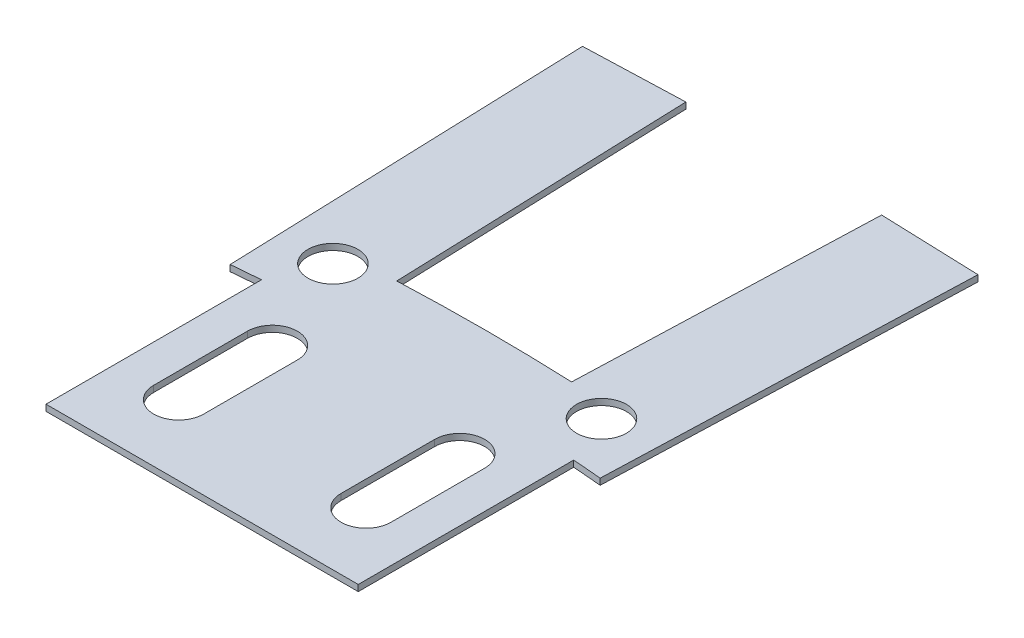
SolidWorks part; units mm, degrees
material "Galvanized Steel"
ref_plane "Front Plane" through (0, 0, 0) normal (0, 0, 1) x (1, 0, 0)
ref_plane "Top Plane" through (0, 0, 0) normal (0, 1, 0) x (1, 0, 0)
ref_plane "Right Plane" through (0, 0, 0) normal (1, 0, 0) x (0, 0, -1)
sketch "Sketch1" plane through (0, 0, 0) normal (0, 1, 0) x (1, 0, 0)
  line L0 (-1000, 0) -> (49000, 0) construction
  line L1 (0, -1000) -> (0, 49000) construction
  line L2 (-500, -866.0254) -> (24500, 42435.2448) construction
  line L3 (-500, 866.0254) -> (24500, -42435.2448) construction
  line L7 (25, 325.8046) -> (25, 291.3046)
  line L8 (25, 291.3046) -> (-25, 291.3046)
  line L9 (29.6237, 325.4167) -> (29.9934, 336.0031)
  line L10 (-25, 325.8046) -> (-25, 291.3046)
  line L11 (29.9934, 336.0031) -> (31.6654, 383.8836)
  line L12 (31.6654, 383.8836) -> (15.6752, 384.442)
  line L13 (15.6752, 384.442) -> (14, 336.4712)
  line L14 (-15.6752, 384.442) -> (-14, 336.4712)
  line L15 (-31.6654, 383.8836) -> (-15.6752, 384.442)
  line L16 (-29.9934, 336.0031) -> (-31.6654, 383.8836)
  line L17 (-29.6237, 325.4167) -> (-29.9934, 336.0031)
  line L18 (-19, 317.5546) -> (-19, 302.5546)
  line L20 (-11, 317.5546) -> (-11, 302.5546)
  line L21 (19, 317.5546) -> (19, 302.5546)
  line L22 (11, 317.5546) -> (11, 302.5546)
  circle A0 centre (0, 0) radius 400 construction
  arc A14 (25, 325.8046) -> (29.6237, 325.4167) centre (0, 0) cw
  arc A15 (-25, 325.8046) -> (-29.6237, 325.4167) centre (0, 0) ccw
  arc A16 (14, 336.4712) -> (-14, 336.4712) centre (0, 0) ccw
  arc A17 (-19, 302.5546) -> (-11, 302.5546) centre (-15, 302.5546) ccw
  circle A19 centre (-21.5, 333.7549) radius 4
  circle A20 centre (21.5, 333.7549) radius 4
  arc A21 (-11, 317.5546) -> (-19, 317.5546) centre (-15, 317.5546) ccw
  arc A22 (19, 302.5546) -> (11, 302.5546) centre (15, 302.5546) cw
  arc A23 (11, 317.5546) -> (19, 317.5546) centre (15, 317.5546) cw
  point P34 (0, 291.3046)
  dimension "D1" = 800
  dimension "D4" = 2
  dimension "D5" = 28
  dimension "D8" = 10
  dimension "D9" = 50
  dimension "D12" = 11.25
  dimension "D13" = 30
  dimension "D14" = 21.5
  dimension "D15" = 8
  dimension "D6" = 16
  dimension "D7" = 336.7623
  dimension "D10" = 8
  dimension "D17" = 8
  dimension "D18" = 4
  dimension "D2" = 60
  dimension "D3" = 60
  dimension "D11" = 34.5
  dimension "D16" = 48
  dimension "D19" = 31.3504
  dimension "D20" = 15
extrude "Boss-Extrude1" add sketch "Sketch1" along normal mid plane 1
